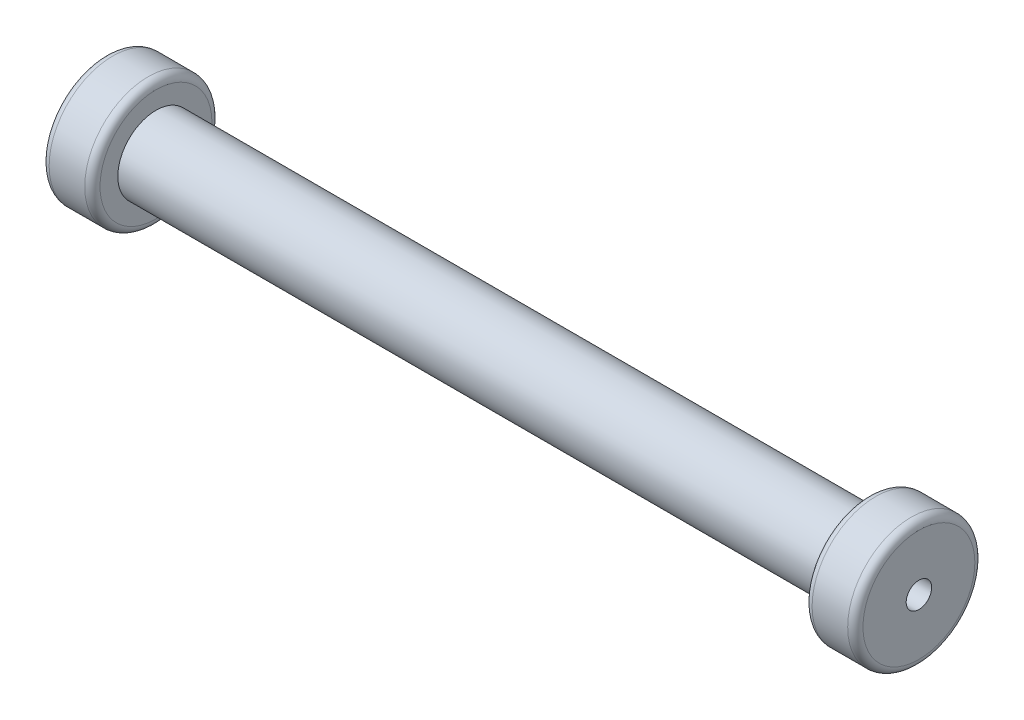
SolidWorks part; units mm, degrees
ref_plane "Front Plane" through (0, 0, 0) normal (0, 0, 1) x (1, 0, 0)
ref_plane "Top Plane" through (0, 0, 0) normal (0, 1, 0) x (1, 0, 0)
ref_plane "Right Plane" through (0, 0, 0) normal (1, 0, 0) x (0, 0, -1)
sketch "Sketch2" plane through (0, 0, 0) normal (0, 1, 0) x (1, 0, 0)
  line L0 (0, 27.0951) -> (0, -27.131) construction
  line L1 (-160, 0) -> (160, 0)
  line L2 (160, 0) -> (160, -25)
  line L3 (-160, 0) -> (-160, -25)
  line L4 (160, -25) -> (140, -25)
  line L5 (-160, -25) -> (-140, -25)
  line L6 (140, -25) -> (140, -15)
  line L7 (-140, -25) -> (-140, -15)
  line L8 (140, -15) -> (-140, -15)
  line L9 (-179.6158, 0) -> (252.8457, 0) construction
  line L10 (179.6158, 0) -> (-252.8457, 0) construction
  point P5 (0, 0)
  point P12 (0, -15)
  dimension "D3" = 20
  dimension "D1" = 140
  dimension "D2" = 25
  dimension "D4" = 15
revolve "Revolve1" add sketch "Sketch2" angle 360 about L9
fillet "Fillet1" radius 3 4 edges at (140, 0, 25) (160, 0, 25) (-160, 0, 25) (-140, 0, 25)
sketch "Sketch3" plane through (160, 0, 0) normal (1, 0, 0) x (0, 0, -1)
  circle A0 centre (0, 0) radius 5
  dimension "D1" = 10
extrude "Cut-Extrude1" cut sketch "Sketch3" against normal through all
